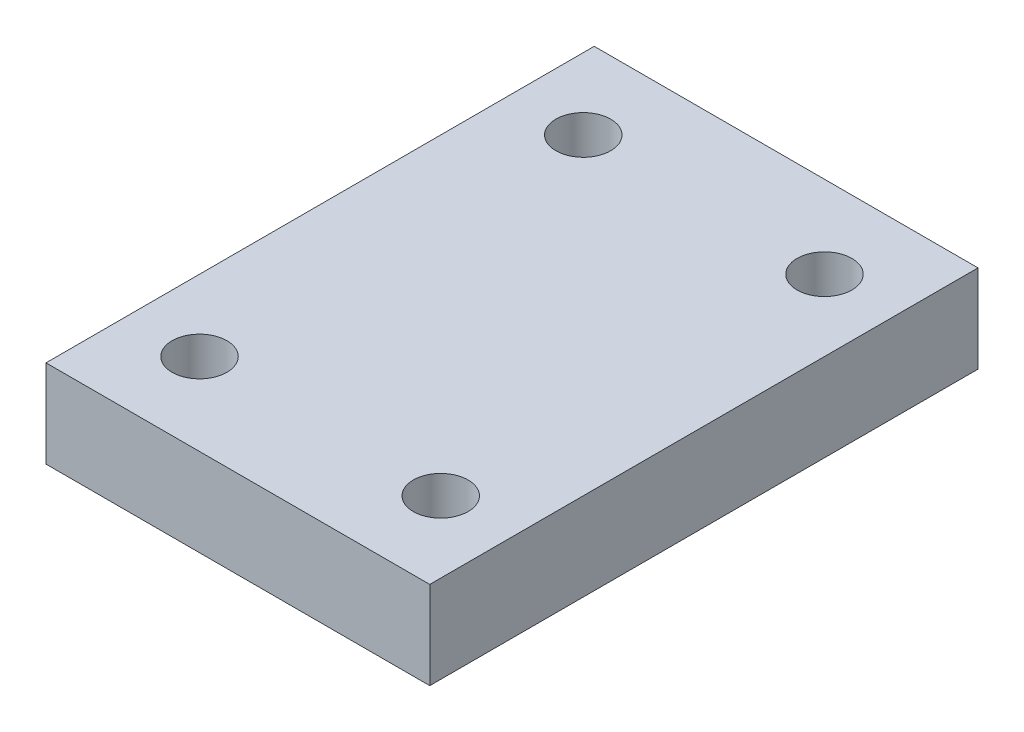
SolidWorks part; units mm, degrees
ref_plane "Front Plane" through (0, 0, 0) normal (0, 0, 1) x (1, 0, 0)
ref_plane "Top Plane" through (0, 0, 0) normal (0, 1, 0) x (1, 0, 0)
ref_plane "Right Plane" through (0, 0, 0) normal (1, 0, 0) x (0, 0, -1)
sketch "Sketch1" plane through (0, 0, 0) normal (0, 1, 0) x (1, 0, 0)
  line L1 (-17.5, 25) -> (17.5, 25)
  line L2 (-17.5, 25) -> (-17.5, -25)
  line L3 (-17.5, -25) -> (17.5, -25)
  line L4 (17.5, 25) -> (17.5, -25)
  line L5 (-17.5, 25) -> (17.5, -25) construction
  line L6 (-17.5, -25) -> (17.5, 25) construction
  circle A0 centre (11, 17.5) radius 2.5
  circle A1 centre (11, -17.5) radius 2.5
  circle A2 centre (-11, 17.5) radius 2.5
  circle A3 centre (-11, -17.5) radius 2.5
  point P0 (0, 0)
  dimension "D3" = 35
  dimension "D5" = 22
  dimension "D1" = 50
  dimension "D2" = 35
  dimension "D4" = 7.5
  dimension "D6" = 6.5
extrude "Boss-Extrude1" add sketch "Sketch1" along normal blind 8
